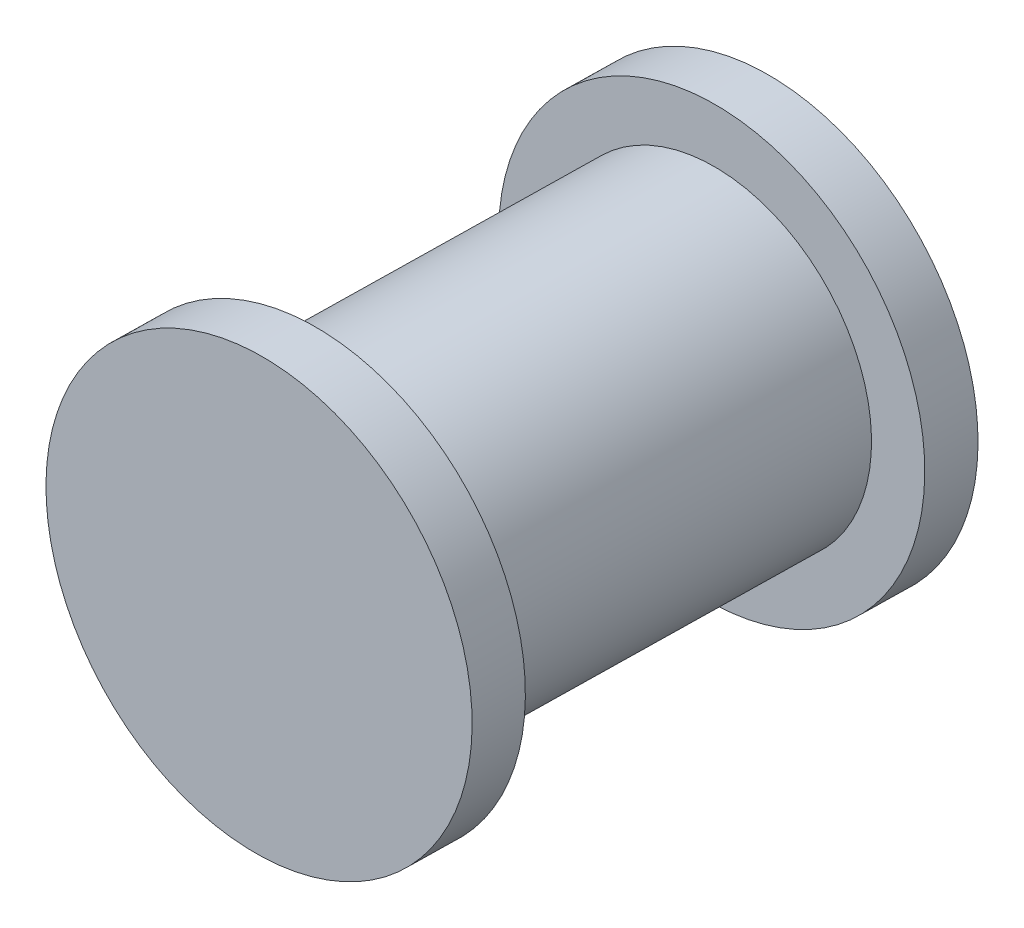
SolidWorks part; units mm, degrees
material "Alumina"
ref_plane "Front Plane" through (0, 0, 0) normal (0, 0, 1) x (1, 0, 0)
ref_plane "Top Plane" through (0, 0, 0) normal (0, 1, 0) x (1, 0, 0)
ref_plane "Right Plane" through (0, 0, 0) normal (1, 0, 0) x (0, 0, -1)
sketch "Sketch1" plane through (0, 0, 0) normal (0, 0, 1) x (1, 0, 0)
  line L0 (0, 0) -> (0, 9.5)
  line L3 (-3, 1) -> (-4, 1)
  line L4 (-4, 1) -> (-4, 0)
  line L5 (-4, 0) -> (0, 0)
  line L6 (0, 9.5) -> (-4, 9.5)
  line L7 (-4, 9.5) -> (-4, 8.5)
  line L8 (-4, 8.5) -> (-3, 8.5)
  line L9 (-3, 8.5) -> (-3, 1)
  dimension "D1" = 9.5
  dimension "D2" = 1
  dimension "D3" = 4
  dimension "D4" = 3
revolve "Revolve1" add sketch "Sketch1" angle 360 about L0
move or copy body "Body-Move/Copy1" bodies to move or copy 101 copy no rotation origin (-2.3466, 4.6121, -2.3466) rotation axis (0.574, 0.5841, 0.574) rotation angle 119.424
